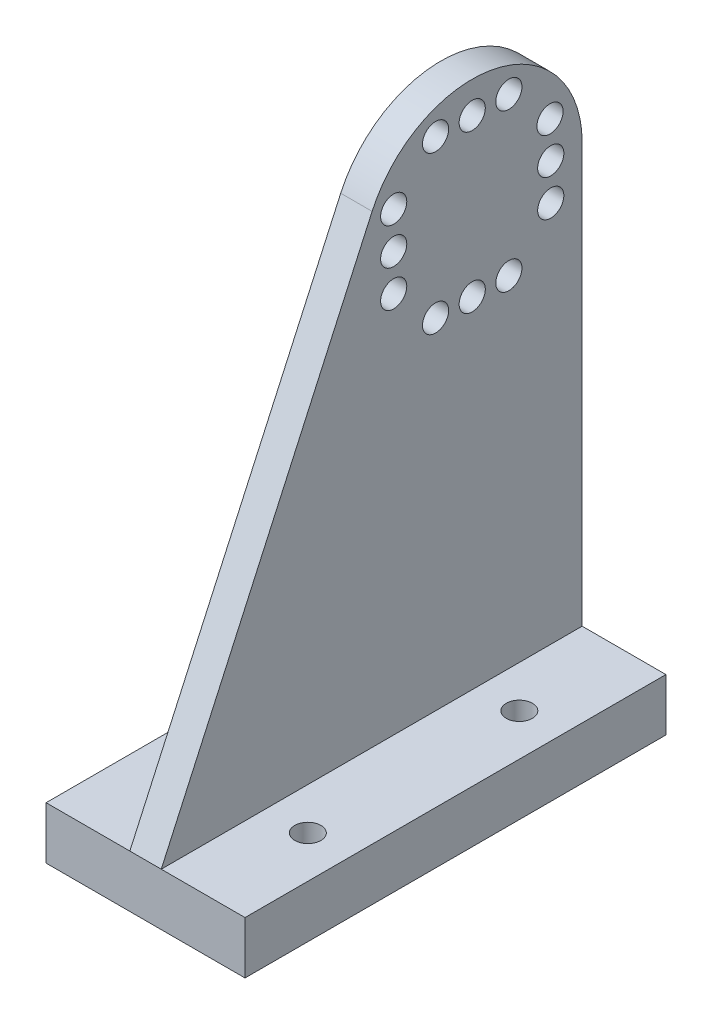
SolidWorks part; units mm, degrees
ref_plane "Front Plane" through (0, 0, 0) normal (0, 0, 1) x (1, 0, 0)
ref_plane "Top Plane" through (0, 0, 0) normal (0, 1, 0) x (1, 0, 0)
ref_plane "Right Plane" through (0, 0, 0) normal (1, 0, 0) x (0, 0, -1)
sketch "Sketch1" plane through (0, 0, 0) normal (1, 0, 0) x (0, 0, -1)
  line L0 (3.5, 7.5) -> (0, 7.5) construction
  line L1 (0, 7.5) -> (-3.5, 7.5) construction
  line L4 (0, 0) -> (0, -7.5) construction
  line L5 (0, -7.5) -> (0, 0) construction
  line L6 (3.5, -7.5) -> (0, -7.5) construction
  line L7 (0, -7.5) -> (-3.5, -7.5) construction
  line L8 (7.4283, 3.4993) -> (7.5, 0) construction
  line L9 (7.5, 0) -> (7.5, -3.5) construction
  line L10 (0, 7.5) -> (0, -7.5) construction
  line L11 (7.5, 0) -> (0, 0) construction
  line L12 (0, 0) -> (0, -7.5) construction
  line L14 (0, 7.5) -> (0, 0) construction
  line L17 (10.5, 0) -> (10.5, -40) construction
  line L18 (10.5, -40) -> (-29.7, -40) construction
  line L19 (-29.7, -40) -> (-9.5601, 4.3421) construction
  line L20 (10.5, 0) -> (10.5, -40)
  line L21 (10.5, -40) -> (-29.7, -40)
  line L22 (-29.7, -40) -> (-9.5601, 4.3421)
  line L23 (0, -7.5) -> (0, 0) construction
  circle A0 centre (0, 0) radius 10.5
  circle A1 centre (-3.5, 7.5) radius 1.25
  circle A2 centre (3.5, 7.5) radius 1.25
  circle A3 centre (7.4283, 3.4993) radius 1.25
  circle A4 centre (7.5, -3.5) radius 1.25
  circle A5 centre (3.5, -7.5) radius 1.25
  circle A6 centre (-3.5, -7.5) radius 1.25
  circle A7 centre (-7.5, -3.5) radius 1.25
  circle A8 centre (-7.5, 3.5) radius 1.25
  circle A9 centre (-7.5, 0) radius 1.25
  circle A10 centre (7.5, 0) radius 1.25
  circle A11 centre (0, -7.5) radius 1.25
  circle A12 centre (0, 7.5) radius 1.25
extrude "Boss-Extrude1" add sketch "Sketch1" along normal blind 3
sketch "Sketch2" plane through (0, -40, 0) normal (0, -1, 0) x (-1, 0, 0)
  line L1 (-3, 10.5) -> (0, 10.5)
  line L2 (-3, 10.5) -> (-3, -29.7)
  line L3 (-3, -29.7) -> (0, -29.7)
  line L4 (0, 10.5) -> (0, -29.7)
extrude "Boss-Extrude2" add sketch "Sketch2" along normal blind 5
sketch "Sketch4" plane through (0, 0, 0) normal (-1, 0, 0) x (0, 0, 1)
  line L0 (29.7, -40) -> (-10.5, -40) construction
  line L1 (-10.5, 0) -> (-10.5, -45) construction
  line L2 (-10.5, -40) -> (-10.5, -45) construction
  line L3 (-10.5, -45) -> (29.7, -45) construction
  line L4 (29.7, -45) -> (29.7, -40) construction
  line L6 (-10.5, -40) -> (29.7, -40)
  line L7 (-10.5, -40) -> (-10.5, -45)
  line L8 (-10.5, -45) -> (29.7, -45)
  line L9 (29.7, -40) -> (29.7, -45)
extrude "Boss-Extrude3" add sketch "Sketch4" along normal blind 8
mirror "Mirror1" about plane through (3, 0, 0) normal (1, 0, 0) of bodies 118 120
delete or keep bodies "Body-Delete/Keep 1" type delete bodies bodies 118
mirror "Mirror2" of bodies 121
delete or keep bodies "Body-Delete/Keep 2" type delete bodies bodies 121
sketch "Sketch7" plane through (3, 0, 0) normal (1, 0, 0) x (0, 0, -1)
  line L1 (-29.7, -40) -> (10.5, -40)
  line L2 (-29.7, -40) -> (-29.7, -45)
  line L3 (-29.7, -45) -> (10.5, -45)
  line L4 (10.5, -40) -> (10.5, -45)
extrude "Boss-Extrude4" add sketch "Sketch7" along normal blind 8
sketch "Sketch8" plane through (0, -40, 0) normal (0, 1, 0) x (1, 0, 0)
  line L0 (7, -29.7) -> (7, 10.5) construction
  line L1 (11, -29.7) -> (3, -29.7) construction
  line L2 (11, 10.5) -> (3, 10.5) construction
  line L3 (7, 10.5) -> (7, 0.5) construction
  line L4 (7, -29.7) -> (7, -19.7) construction
  circle A0 centre (7, 0.5) radius 1.25
  circle A1 centre (7, -19.7) radius 1.25
extrude "Cut-Extrude1" cut sketch "Sketch8" against normal blind 8
